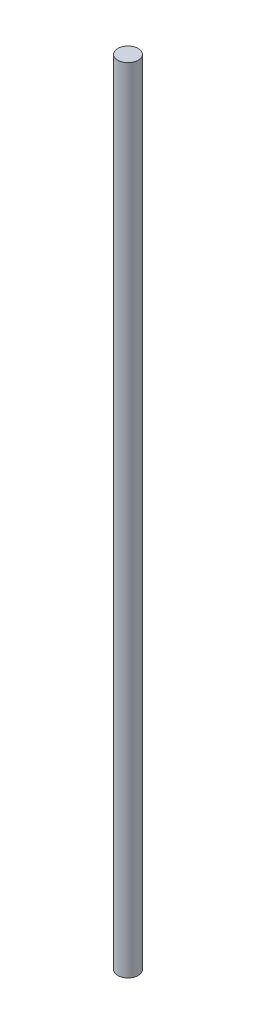
SolidWorks part; units mm, degrees
ref_plane "Front" through (0, 0, 0) normal (0, 0, 1) x (1, 0, 0)
ref_plane "Top" through (0, 0, 0) normal (0, 1, 0) x (1, 0, 0)
ref_plane "Right" through (0, 0, 0) normal (1, 0, 0) x (0, 0, -1)
sketch "Sketch1" plane through (0, 0, 0) normal (0, 1, 0) x (1, 0, 0)
  circle A0 centre (0, 0) radius 4
  dimension "D1" = 8
extrude "Boss-Extrude1" add sketch "Sketch1" along normal mid plane 310
